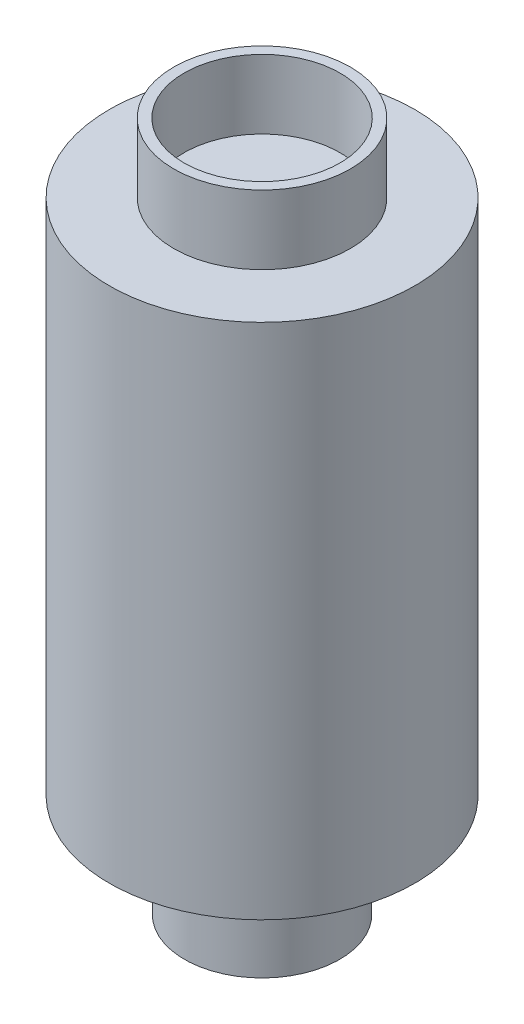
SolidWorks part; units mm, degrees
ref_plane "Front Plane" through (0, 0, 0) normal (0, 0, 1) x (1, 0, 0)
ref_plane "Top Plane" through (0, 0, 0) normal (0, 1, 0) x (1, 0, 0)
ref_plane "Right Plane" through (0, 0, 0) normal (1, 0, 0) x (0, 0, -1)
sketch "Sketch1" plane through (0, 0, 0) normal (0, 1, 0) x (1, 0, 0)
  circle A0 centre (0, 0) radius 11.3
  circle A1 centre (0, 0) radius 12.8
  dimension "D1" = 22.6
  dimension "D2" = 25.6
extrude "Boss-Extrude1" add sketch "Sketch1" along normal blind 10
sketch "Sketch2" plane through (0, 0, 0) normal (0, -1, 0) x (1, 0, 0)
  circle A0 centre (0, 0) radius 22.1391
extrude "Boss-Extrude2" add sketch "Sketch2" along normal blind 75
sketch "Sketch3" plane through (0, -75, 0) normal (0, -1, 0) x (1, 0, 0)
  circle A0 centre (0, 0) radius 11.25
  circle A1 centre (0, 0) radius 8.25
  dimension "D1" = 22.5
  dimension "D2" = 3
extrude "Boss-Extrude3" add sketch "Sketch3" along normal blind 15
